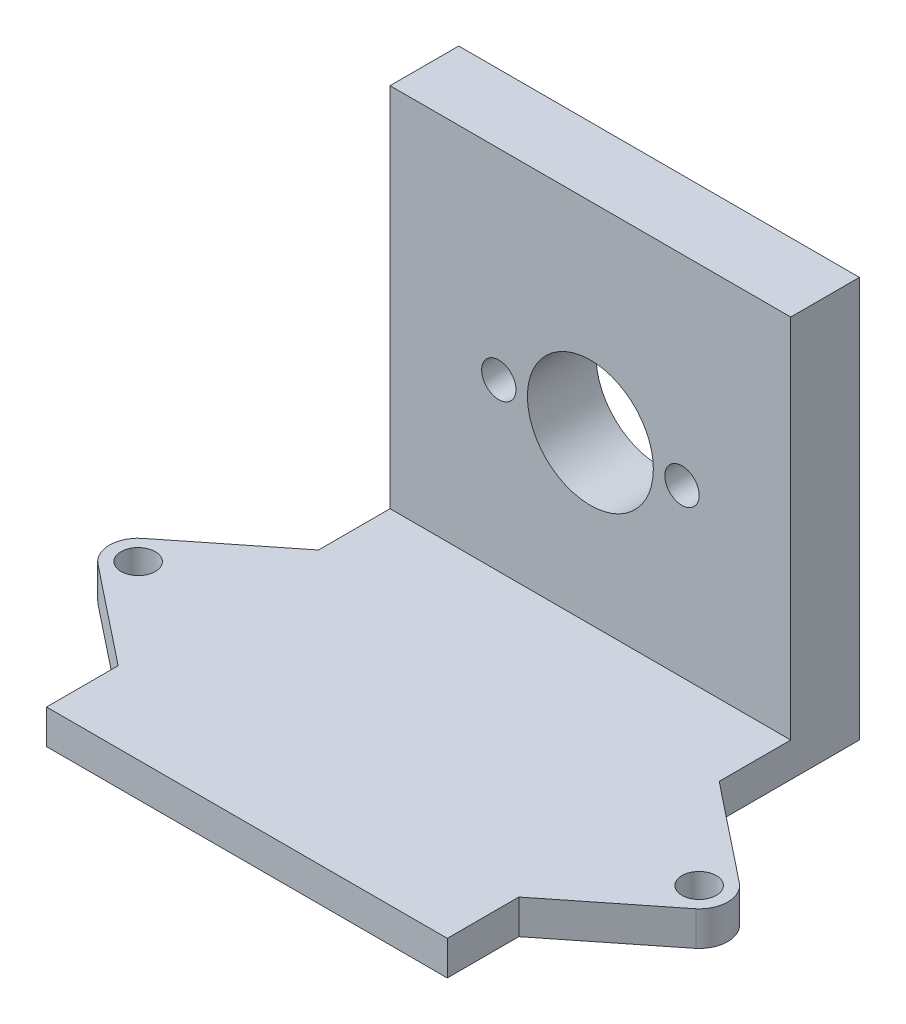
SolidWorks part; units mm, degrees
ref_plane "Front Plane" through (0, 0, 0) normal (0, 0, 1) x (1, 0, 0)
ref_plane "Top Plane" through (0, 0, 0) normal (0, 1, 0) x (1, 0, 0)
ref_plane "Right Plane" through (0, 0, 0) normal (1, 0, 0) x (0, 0, -1)
sketch "Sketch1" plane through (0, 0, 0) normal (0, 0, 1) x (1, 0, 0)
  line L1 (-17.5, -17.5) -> (17.5, -17.5)
  line L2 (-17.5, -17.5) -> (-17.5, 17.5)
  line L3 (-17.5, 17.5) -> (17.5, 17.5)
  line L4 (17.5, -17.5) -> (17.5, 17.5)
  line L5 (-17.5, -17.5) -> (17.5, 17.5) construction
  line L6 (-17.5, 17.5) -> (17.5, -17.5) construction
  circle A0 centre (0, 0) radius 5.5
  circle A1 centre (8, 0) radius 1.5
  circle A2 centre (-8, 0) radius 1.5
  point P0 (0, 0)
  dimension "D3" = 11
  dimension "D4" = 3
  dimension "D5" = 3
  dimension "D1" = 35
  dimension "D2" = 35
  dimension "D6" = 16
  dimension "D7" = 8
extrude "Boss-Extrude1" add sketch "Sketch1" along normal blind 6
sketch "Sketch2" plane through (0, 0, 6) normal (0, 0, 1) x (1, 0, 0)
  line L0 (17.5, -17.5) -> (17.5, 17.5) construction
  line L1 (-17.5, -17.5) -> (17.5, -17.5)
  line L2 (-17.5, -17.5) -> (-17.5, -14.5)
  line L3 (-17.5, -14.5) -> (17.5, -14.5)
  line L4 (17.5, -17.5) -> (17.5, -14.5)
  dimension "D1" = 3
extrude "Boss-Extrude2" add sketch "Sketch2" along normal blind 30
sketch "Sketch3" plane through (0, -14.5, 0) normal (0, 1, 0) x (1, 0, 0)
  line L0 (-36.761, -21) -> (34.9288, -21) construction
  line L1 (17.5, -36) -> (17.5, -6) construction
  line L2 (17.5, -29.75) -> (17.5, -12.25)
  line L3 (0, 6.1097) -> (0, -50.0106) construction
  line L5 (-17.5, -36) -> (-17.5, -6) construction
  line L6 (17.5, -29.75) -> (26.1141, -22.9091)
  line L7 (17.5, -12.25) -> (26.1141, -19.0909)
  line L8 (-17.5, -29.75) -> (-17.5, -12.25)
  line L9 (-17.5, -12.25) -> (-26.1141, -19.0909)
  line L10 (-17.5, -29.75) -> (-26.1141, -22.9091)
  arc A0 (26.1141, -22.9091) -> (26.1141, -19.0909) centre (24.5, -21) ccw
  circle A2 centre (24.5, -21) radius 1.5
  circle A8 centre (-24.5, -21) radius 1.5
  arc A9 (-26.1141, -22.9091) -> (-26.1141, -19.0909) centre (-24.5, -21) cw
  dimension "D2" = 5
  dimension "D3" = 17.5
  dimension "D4" = 3
  dimension "D1" = 7
  dimension "D5" = 11
  dimension "D6" = 11
extrude "Boss-Extrude3" add sketch "Sketch3" against normal up to surface (3 mm away) up to face at (0, -17.5, 18)
